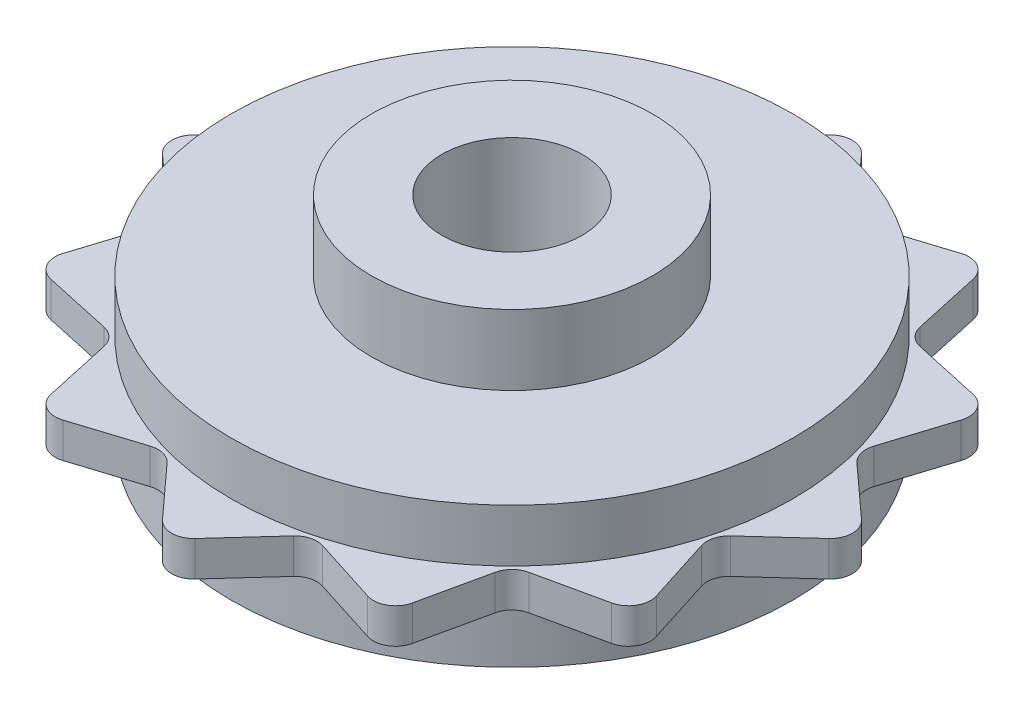
SolidWorks part; units mm, degrees
material "1023 Carbon Steel Sheet (SS)"
ref_plane "Front Plane" through (0, 0, 0) normal (0, 0, 1) x (1, 0, 0)
ref_plane "Top Plane" through (0, 0, 0) normal (0, 1, 0) x (1, 0, 0)
ref_plane "Right Plane" through (0, 0, 0) normal (1, 0, 0) x (0, 0, -1)
sketch "Sketch1" plane through (0, 0, 0) normal (0, 1, 0) x (1, 0, 0)
  circle A0 centre (0, 0) radius 6.35
  dimension "D1" = 12.7
extrude "Boss-Extrude1" add sketch "Sketch1" along normal mid plane 12.7 from surface at 0 starting at plane "Top Plane"
sketch "Sketch2" plane through (0, 0, 0) normal (0, 1, 0) x (1, 0, 0)
  circle A0 centre (0, 0) radius 12.7
  dimension "D1" = 25.4
extrude "Boss-Extrude2" add sketch "Sketch2" along normal mid plane 6.35 from surface at 0 starting at plane "Top Plane"
ref_plane "Plane1" through (0, 0, 0) normal (0, 1, 0) x (1, 0, 0)
sketch "Sketch3" plane through (0, 0, 0) normal (0, 1, 0) x (1, 0, 0)
  line L0 (0, 0) -> (0, -15.875) construction
  line L1 (0, 0) -> (-4.4774, -16.7099) construction
  line L2 (-3.287, -12.2673) -> (0, -15.875) construction
  line L3 (0, 0) -> (-9.078, -15.7235) construction
  line L4 (-3.287, -12.2673) -> (-7.9375, -13.7482) construction
  line L5 (-6.8917, -13.4151) -> (-3.8979, -12.4618)
  line L6 (-2.8552, -12.7412) -> (-0.7392, -15.0637)
  line L7 (-7.6951, -13.3283) -> (-6.35, -10.9985)
  line L8 (-6.35, -10.9985) -> (0, -12.7)
  line L9 (0, -12.7) -> (0, -15.3902)
  circle A0 centre (0, 0) radius 12.7 construction
  arc A1 (-0.7392, -15.0637) -> (0, -15.3902) centre (0, -14.3902) ccw
  circle A2 centre (0, 0) radius 15.875 construction
  arc A3 (-7.6951, -13.3283) -> (-6.8917, -13.4151) centre (-7.1951, -12.4623) ccw
  arc A4 (-3.8979, -12.4618) -> (-2.8552, -12.7412) centre (-3.5944, -13.4146) cw
  point P14 (-0.7392, -15.0637)
  dimension "D3" = 1
  dimension "D2" = 3.175
  dimension "D5" = 1
  dimension "D6" = 1
  dimension "D1" = 15
  dimension "D4" = 15
extrude "Boss-Extrude3" add sketch "Sketch3" along normal mid plane 1.5875
pattern_circular "CirPattern1" count 12 over 360 about axis through (0, 0, 0) along (0, 1, 0) of "Boss-Extrude3"
sketch "Sketch4" plane through (0, 6.35, 0) normal (0, 1, 0) x (1, 0, 0)
  circle A0 centre (0, 0) radius 3.175
  dimension "D1" = 6.35
extrude "Cut-Extrude1" cut sketch "Sketch4" against normal through all
